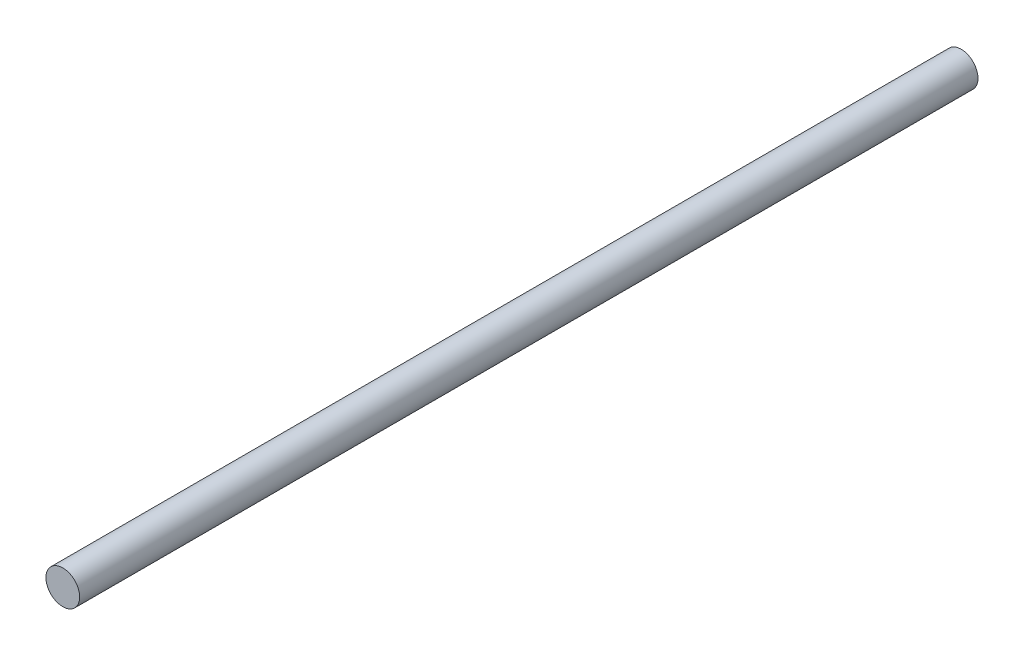
SolidWorks part; units mm, degrees
ref_plane "Front Plane" through (0, 0, 0) normal (0, 0, 1) x (1, 0, 0)
ref_plane "Top Plane" through (0, 0, 0) normal (0, 1, 0) x (1, 0, 0)
ref_plane "Right Plane" through (0, 0, 0) normal (1, 0, 0) x (0, 0, -1)
sketch "Sketch1" plane through (0, 0, 0) normal (0, 0, 1) x (1, 0, 0)
  circle A0 centre (0, 0) radius 7.5
  dimension "D1" = 15
extrude "Boss-Extrude1" add sketch "Sketch1" along normal blind 400 contours A0
